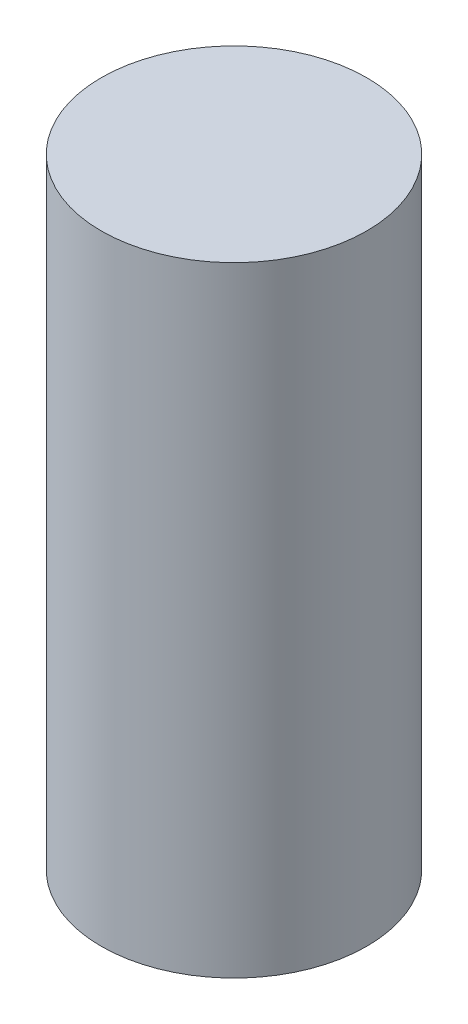
SolidWorks part; units mm, degrees
ref_plane "Front Plane" through (0, 0, 0) normal (0, 0, 1) x (1, 0, 0)
ref_plane "Top Plane" through (0, 0, 0) normal (0, 1, 0) x (1, 0, 0)
ref_plane "Right Plane" through (0, 0, 0) normal (1, 0, 0) x (0, 0, -1)
other "Configuration Table"
sketch "Sketch1" plane through (0, 0, 0) normal (0, 1, 0) x (1, 0, 0)
  circle A0 centre (50, 50) radius 6
extrude "TOPPING_ayar_mil_1" add sketch "Sketch1" along normal blind 28 from offset 12 separate body
